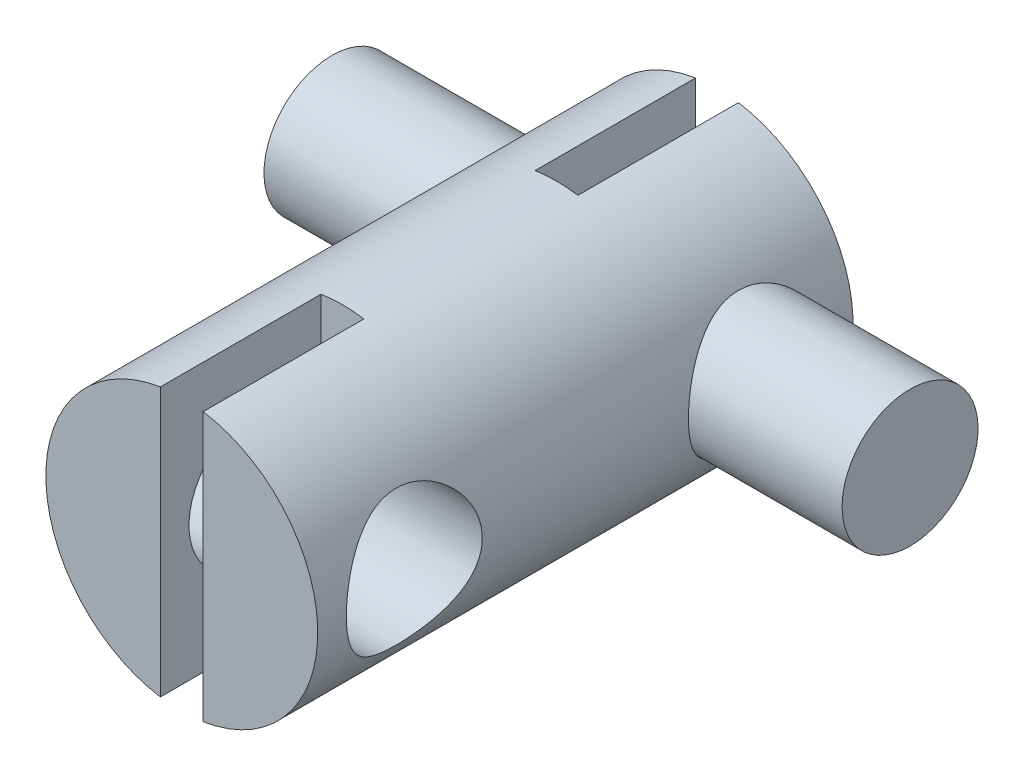
SolidWorks part; units mm, degrees
ref_plane "Front Plane" through (0, 0, 0) normal (0, 0, 1) x (1, 0, 0)
ref_plane "Top Plane" through (0, 0, 0) normal (0, 1, 0) x (1, 0, 0)
ref_plane "Right Plane" through (0, 0, 0) normal (1, 0, 0) x (0, 0, -1)
sketch "Sketch1" plane through (0, 0, 0) normal (0, 0, 1) x (1, 0, 0)
  circle A0 centre (0, 0) radius 25.4
extrude "Boss-Extrude1" add sketch "Sketch1" along normal blind 50
sketch "Sketch2" plane through (0, 0, 50) normal (0, 0, 1) x (1, 0, 0)
  line L1 (-4, 26.8563) -> (4, 26.8563)
  line L2 (-4, 26.8563) -> (-4, -29.7614)
  line L3 (-4, -29.7614) -> (4, -29.7614)
  line L4 (4, 26.8563) -> (4, -29.7614)
extrude "Cut-Extrude1" cut sketch "Sketch2" against normal blind 30
sketch "Sketch3" plane through (4, 0, 0) normal (-1, 0, 0) x (0, 0, 1)
  circle A0 centre (31.9544, 0) radius 12.7
  point P2 (31.9544, 0)
extrude "Cut-Extrude2" cut sketch "Sketch3" against normal mid plane 70
mirror "Mirror1" about plane through (0, 0, 0) normal (0, 0, 1) of bodies 103 108
sketch "Sketch4" plane through (4, 0, 0) normal (-1, 0, 0) x (0, 0, 1)
  circle A0 centre (-32.0544, 0) radius 12.7
  point P2 (-33.523, 0)
  point P3 (0, 0)
  point P4 (-32.0544, 0)
extrude "Boss-Extrude2" add sketch "Sketch4" against normal blind 50
sketch "Sketch5" plane through (-4, 0, 0) normal (1, 0, 0) x (0, 0, -1)
  circle A0 centre (32.0544, 0) radius 12.7
  point P3 (32.0544, 0)
extrude "Boss-Extrude3" add sketch "Sketch5" against normal blind 50
